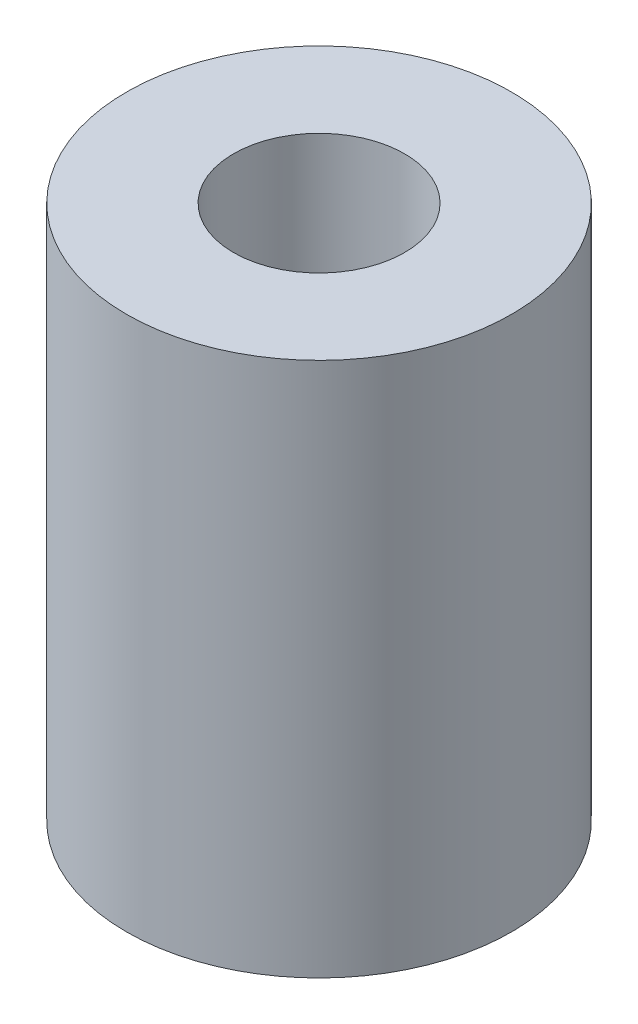
SolidWorks part; units mm, degrees
ref_plane "Front Plane" through (0, 0, 0) normal (0, 0, 1) x (1, 0, 0)
ref_plane "Top Plane" through (0, 0, 0) normal (0, 1, 0) x (1, 0, 0)
ref_plane "Right Plane" through (0, 0, 0) normal (1, 0, 0) x (0, 0, -1)
sketch "Sketch1" plane through (0, 0, 0) normal (0, 1, 0) x (1, 0, 0)
  circle A0 centre (0, 0) radius 4
  circle A1 centre (0, 0) radius 9
  dimension "D1" = 18
  dimension "D2" = 8
extrude "Boss-Extrude1" add sketch "Sketch1" along normal blind 25
